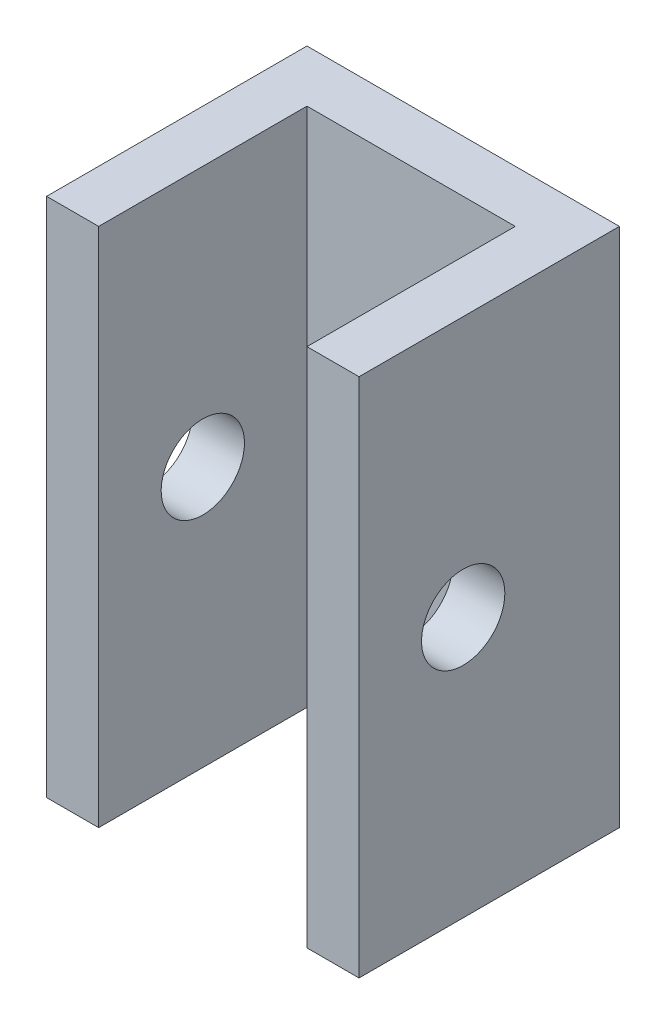
SolidWorks part; units mm, degrees
ref_plane "Front Plane" through (0, 0, 0) normal (0, 0, 1) x (1, 0, 0)
ref_plane "Top Plane" through (0, 0, 0) normal (0, 1, 0) x (1, 0, 0)
ref_plane "Right Plane" through (0, 0, 0) normal (1, 0, 0) x (0, 0, -1)
sketch "Sketch1" plane through (0, 0, 0) normal (0, 0, 1) x (1, 0, 0)
  line L1 (-15, -25) -> (15, -25)
  line L2 (-15, -25) -> (-15, 25)
  line L3 (-15, 25) -> (15, 25)
  line L4 (15, -25) -> (15, 25)
  line L5 (-15, -25) -> (15, 25) construction
  line L6 (-15, 25) -> (15, -25) construction
  point P0 (0, 0)
  dimension "D1" = 50
  dimension "D2" = 30
extrude "Boss-Extrude1" add sketch "Sketch1" along normal blind 5
sketch "Sketch2" plane through (0, 0, 5) normal (0, 0, 1) x (1, 0, 0)
  line L0 (-15, -25) -> (15, -25) construction
  line L1 (-15, 25) -> (-10, 25)
  line L2 (-15, 25) -> (-15, -25)
  line L3 (-15, -25) -> (-10, -25)
  line L4 (-10, 25) -> (-10, -25)
  line L6 (15, 25) -> (10, 25)
  line L7 (15, 25) -> (15, -25)
  line L8 (15, -25) -> (10, -25)
  line L9 (10, 25) -> (10, -25)
  dimension "D1" = 5
  dimension "D2" = 5
extrude "Boss-Extrude2" add sketch "Sketch2" along normal blind 20
sketch "Sketch3" plane through (15, 0, 0) normal (1, 0, 0) x (0, 0, -1)
  line L0 (-25, -25) -> (-25, 25) construction
  line L1 (-25, -25) -> (0, -25) construction
  circle A0 centre (-15, 0) radius 4
  dimension "D3" = 8
  dimension "D1" = 10
  dimension "D2" = 25
extrude "Cut-Extrude1" cut sketch "Sketch3" against normal through all
equation "\"D1@Boss-Extrude2\" = \"t_thigh\""
equation "\"D1@Sketch3\"= \"t_thigh\" / 2"
equation "\"t_thigh\"= 0.0200m"
